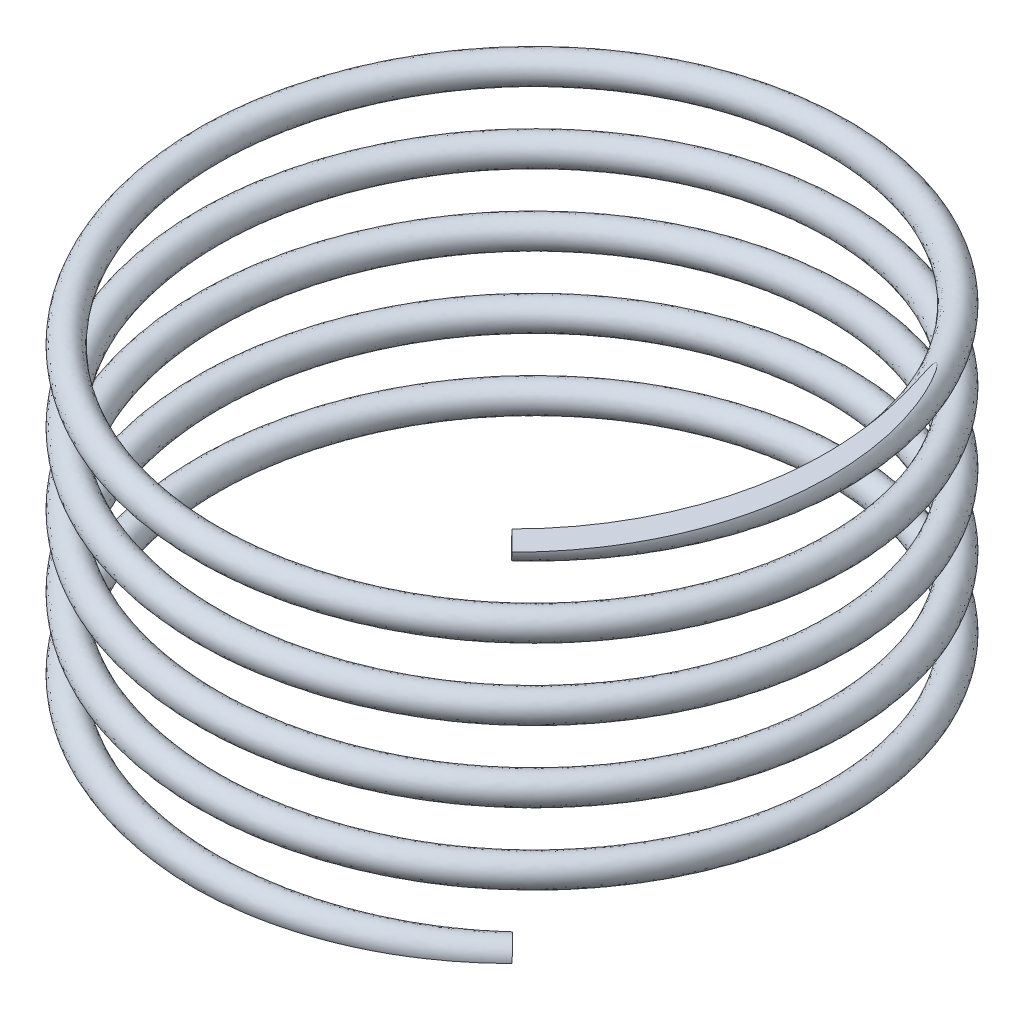
SolidWorks part; units mm, degrees
material "AISI 304"
ref_plane "Front Plane" through (0, 0, 0) normal (0, 0, 1) x (1, 0, 0)
ref_plane "Top Plane" through (0, 0, 0) normal (0, 1, 0) x (1, 0, 0)
ref_plane "Right Plane" through (0, 0, 0) normal (1, 0, 0) x (0, 0, -1)
sketch "Sketch1" plane through (0, 0, 0) normal (0, 1, 0) x (1, 0, 0)
  circle A0 centre (0, 0) radius 8.85
  dimension "D1" = 17.7
curve "Helix/Spiral1" pitch 2 height 10 turns 5
ref_plane "Plane1" through (6.2579, 0, 6.2579) normal (0.7066, -0.0359, -0.7066) x (-0.7074, -0.0555, -0.7046)
sketch "Sketch2" plane through (6.2579, 0, 6.2579) normal (0.7066, -0.0359, -0.7066) x (-0.7074, -0.0555, -0.7046)
  circle A0 centre (0, 0) radius 0.4
  dimension "D1" = 0.8
sweep "Sweep1" add profiles "Sketch2" path "Helix/Spiral1"
sketch "Sketch3" plane through (0, 0, 0) normal (1, 0, 0) x (0, 0, -1)
  line L0 (-9.5, -10) -> (-9.5, 0)
  line L1 (-9.5, -10) -> (9.5, -10)
  line L2 (-9.5, 0) -> (9.5, 0)
  line L3 (9.5, -10) -> (9.5, 0)
  line L4 (-9.5, -10) -> (9.5, 0) construction
  line L5 (-9.5, 0) -> (9.5, -10) construction
  point P1 (0, -5)
  dimension "D1" = 10
  dimension "D2" = 19
extrude "Cut-Extrude1" cut sketch "Sketch3" against normal through all both and the other way through all flip side to cut
sketch "Sketch4" plane through (0, 0, 0) normal (0, 0, 1) x (1, 0, 0)
  line L0 (0, 0) -> (0, -16.19) construction
